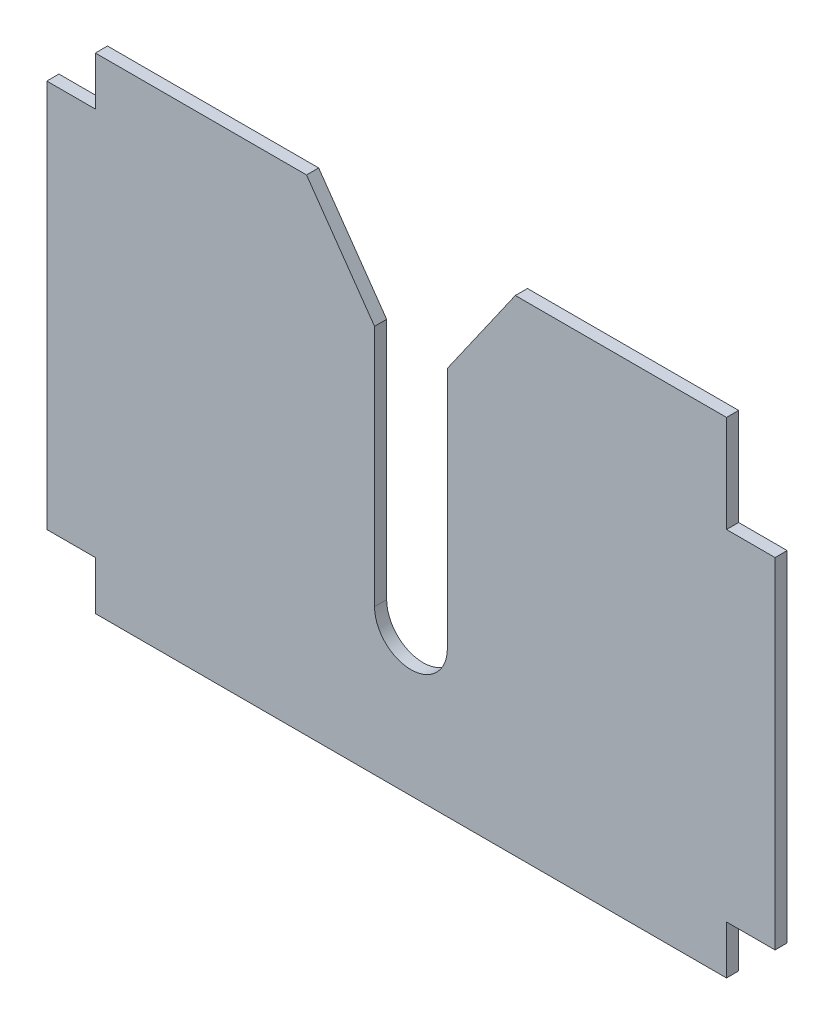
SolidWorks part; units mm, degrees
ref_plane "Front Plane" through (0, 0, 0) normal (0, 0, 1) x (1, 0, 0)
ref_plane "Top Plane" through (0, 0, 0) normal (0, 1, 0) x (1, 0, 0)
ref_plane "Right Plane" through (0, 0, 0) normal (1, 0, 0) x (0, 0, -1)
sketch "Sketch1" plane through (0, 0, 0) normal (0, 0, 1) x (1, 0, 0)
  line L1 (-150, 100) -> (150, 100)
  line L2 (-150, 100) -> (-150, -100)
  line L3 (-150, -100) -> (150, -100)
  line L4 (150, 100) -> (150, -100)
  line L5 (-150, 100) -> (150, -100) construction
  line L6 (-150, -100) -> (150, 100) construction
  point P0 (0, 0)
  dimension "D1" = 300
  dimension "D2" = 200
extrude "Boss-Extrude1" add sketch "Sketch1" along normal blind 5
sketch "Sketch3" plane through (0, 0, 5) normal (0, 0, 1) x (1, 0, 0)
  line L1 (-150, -100) -> (-130, -100)
  line L2 (-150, -100) -> (-150, -80)
  line L3 (-150, -80) -> (-130, -80)
  line L4 (-130, -100) -> (-130, -80)
  line L5 (-150, 100) -> (-130, 100)
  line L6 (-150, 100) -> (-150, 60)
  line L7 (-150, 60) -> (-130, 60)
  line L8 (-130, 100) -> (-130, 60)
  line L9 (150, 100) -> (130, 100)
  line L10 (150, 100) -> (150, 60)
  line L11 (150, 60) -> (130, 60)
  line L12 (130, 100) -> (130, 60)
  line L13 (150, -100) -> (130, -100)
  line L14 (150, -100) -> (150, -80)
  line L15 (150, -80) -> (130, -80)
  line L16 (130, -100) -> (130, -80)
  dimension "D1" = 20
  dimension "D2" = 20
  dimension "D3" = 40
extrude "Cut-Extrude1" cut sketch "Sketch3" against normal blind 5
sketch "Sketch4" plane through (0, 0, 5) normal (0, 0, 1) x (1, 0, 0)
  line L0 (130, 100) -> (-130, 100) construction
  line L1 (-15, -40) -> (-15, 60)
  line L2 (15, -40) -> (15, 60)
  line L3 (-43.0083, 100) -> (-15, 60)
  line L4 (15, 60) -> (43.0083, 100)
  line L5 (0, -40) -> (0, -15.2103) construction
  line L7 (-43.0083, 100) -> (43.0083, 100)
  arc A0 (-15, -40) -> (15, -40) centre (0, -40) ccw
  point P15 (-130, 60)
  dimension "D2" = 30
  dimension "D1" = 140
  dimension "D3" = 70
extrude "Cut-Extrude2" cut sketch "Sketch4" against normal blind 10 contours L4 L7 L3 L1 A0 L2
sketch "Sketch5" plane through (0, 0, 5) normal (0, 0, 1) x (1, 0, 0)
  line L0 (-150, 60) -> (-150, -80) construction
  line L1 (-130, 60) -> (-150, 60)
  line L2 (-130, 60) -> (-130, 80)
  line L3 (-130, 80) -> (-150, 80)
  line L4 (-150, 60) -> (-150, 80)
  dimension "D1" = 20
extrude "Boss-Extrude2" add sketch "Sketch5" against normal blind 5
